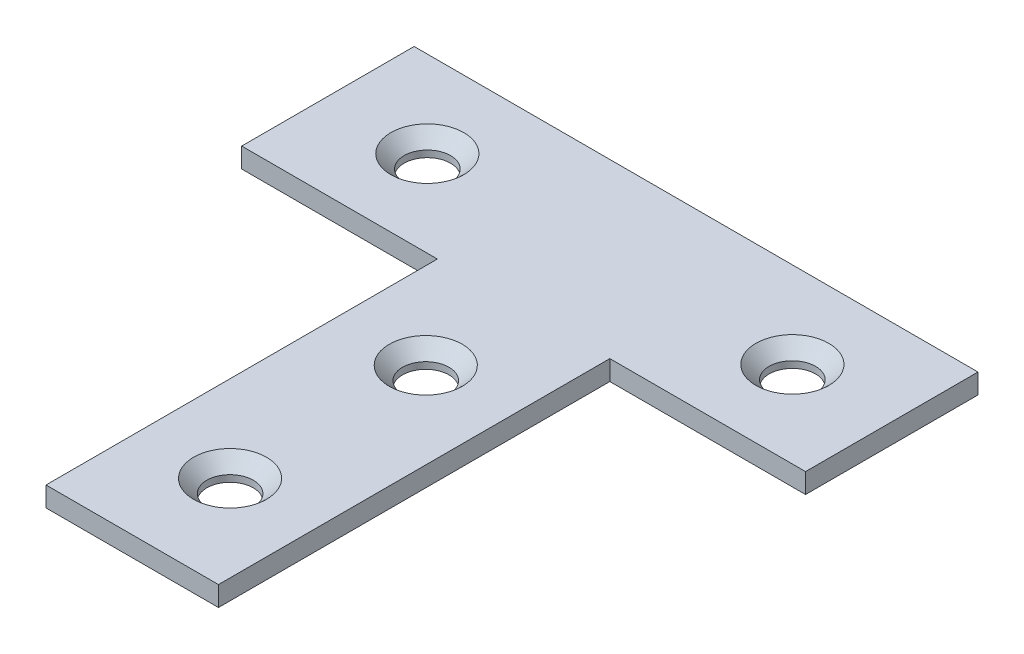
SolidWorks part; units mm, degrees
ref_plane "Front Plane" through (0, 0, 0) normal (0, 0, 1) x (1, 0, 0)
ref_plane "Top Plane" through (0, 0, 0) normal (0, 1, 0) x (1, 0, 0)
ref_plane "Right Plane" through (0, 0, 0) normal (1, 0, 0) x (0, 0, -1)
sketch "Sketch1" plane through (0, 0, 0) normal (0, 1, 0) x (1, 0, 0)
  line L0 (21.25, 17.8485) -> (-21.25, 17.8485)
  line L1 (-21.25, 17.8485) -> (-21.25, 4.8485)
  line L2 (-21.25, 4.8485) -> (-6.5, 4.8485)
  line L3 (-6.5, 4.8485) -> (-6.5, -24.6515)
  line L4 (-6.5, -24.6515) -> (6.5, -24.6515)
  line L5 (0, 29.4672) -> (0, -36.4996) construction
  line L6 (6.5, 4.8485) -> (6.5, -24.6515)
  line L7 (21.25, 4.8485) -> (6.5, 4.8485)
  line L8 (21.25, 17.8485) -> (21.25, 4.8485)
  point P10 (0, -24.6515)
  point P13 (0, 17.8485)
  dimension "D1" = 42.5
  dimension "D2" = 13
  dimension "D3" = 42.5
  dimension "D4" = 13
extrude "Boss-Extrude1" add sketch "Sketch1" along normal blind 1.5 contours L0 L1 L2 L3 L4 L6 L7 L8
sketch "Sketch2" plane through (0, 1.5, 0) normal (0, 1, 0) x (1, 0, 0)
  line L0 (-6.5, -9.9015) -> (6.5, -9.9015) construction
  line L3 (0, 4.8485) -> (0, -9.9015) construction
  line L6 (-6.5, 4.8485) -> (-6.5, -24.6515) construction
  line L7 (6.5, 4.8485) -> (6.5, -24.6515) construction
  line L9 (-6.5, 4.8485) -> (6.5, 4.8485) construction
  circle A0 centre (-13.7568, 11.3485) radius 1.75
  circle A1 centre (13.7568, 11.3485) radius 1.75
  circle A3 centre (0, -2.5265) radius 1.75
  circle A4 centre (0, -17.2765) radius 1.75
extrude "Cut-Extrude1" cut sketch "Sketch2" against normal through all both and the other way through all
chamfer "Chamfer2" distance 1 angle 45 1 edges at (-13.7568, 1.5, -13.0985)
chamfer "Chamfer4" distance 1 angle 45 3 edges at (0, 1.5, 15.5265) (0, 1.5, 0.7765) (13.7568, 1.5, -13.0985)
